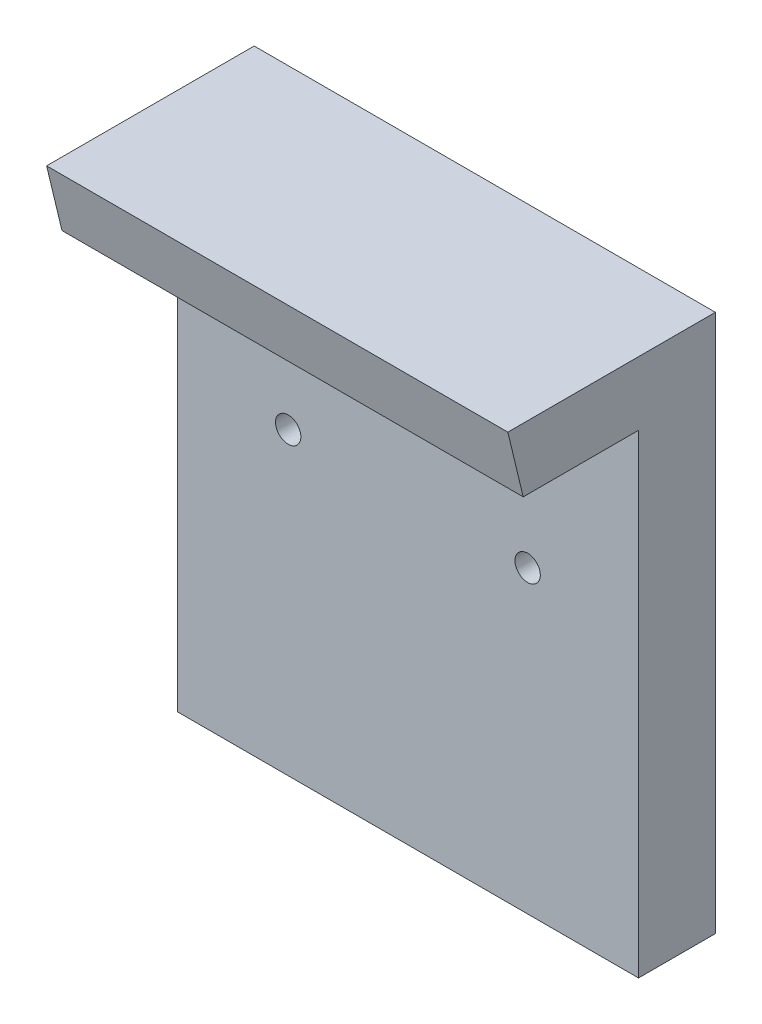
SolidWorks part; units mm, degrees
ref_plane "Plan de face" through (0, 0, 0) normal (0, 0, 1) x (1, 0, 0)
ref_plane "Plan de dessus" through (0, 0, 0) normal (0, 1, 0) x (1, 0, 0)
ref_plane "Plan de droite" through (0, 0, 0) normal (1, 0, 0) x (0, 0, -1)
sketch "Esquisse1" plane through (0, 0, 0) normal (0, 0, 1) x (1, 0, 0)
  line L1 (-26.9236, 19.3151) -> (33.0764, 19.3151)
  line L2 (-26.9236, 19.3151) -> (-26.9236, -50.6849)
  line L3 (-26.9236, -50.6849) -> (33.0764, -50.6849)
  line L4 (33.0764, 19.3151) -> (33.0764, -50.6849)
  dimension "D1" = 60
  dimension "D2" = 70
extrude "Boss.-Extru.1" add sketch "Esquisse1" along normal blind 10
sketch "Esquisse2" plane through (33.0764, 0, 0) normal (1, 0, 0) x (0, 0, -1)
  line L0 (-27, 19.3151) -> (-25, 11.0188)
  line L1 (-10, 19.3151) -> (-27, 19.3151)
  line L2 (-10, 19.3151) -> (-10, 11.0188)
  line L3 (-10, 11.0188) -> (-25, 11.0188)
  dimension "D1" = 17
  dimension "D2" = 15
extrude "Boss.-Extru.2" add sketch "Esquisse2" against normal blind 60
sketch "Esquisse3" plane through (0, 0, 0) normal (0, 0, -1) x (-1, 0, 0)
  circle A0 centre (-18.6514, -11.6849) radius 3.3
  circle A1 centre (12.4986, -11.6849) radius 2.5898
hole_wizard "Trou taraudé M41" positions "Esquisse3D1" profile "Esquisse4" tap size "M4" standard "ISO"
sketch3d "Esquisse3D1"
  point P0 (18.6514, -11.6849, 0)
  point P3 (-12.4986, -11.6849, 0)
sketch "Esquisse4" plane through (18.6514, -11.6849, 0) normal (1, 0, 0) x (0, 1, 0)
  line L0 (0, 0) -> (0, 12.4914)
  line L1 (0, 12.4914) -> (1.65, 11.5)
  line L2 (1.65, 11.5) -> (1.65, 0)
  line L5 (1.65, 0) -> (0, 0)
  line L10 (0, 12.4914) -> (-1.65, 11.5) construction
  line L11 (0, -6.35) -> (0, 107.95) construction
  dimension "Diamètre du trou pour taraudage" = 3.3
  dimension "Profondeur du trou pour taraudage" = 11.5
  dimension "Angle de pointe" = 118
cosmetic thread "Filetage de perçage1"
cosmetic thread "Filetage de perçage2"
